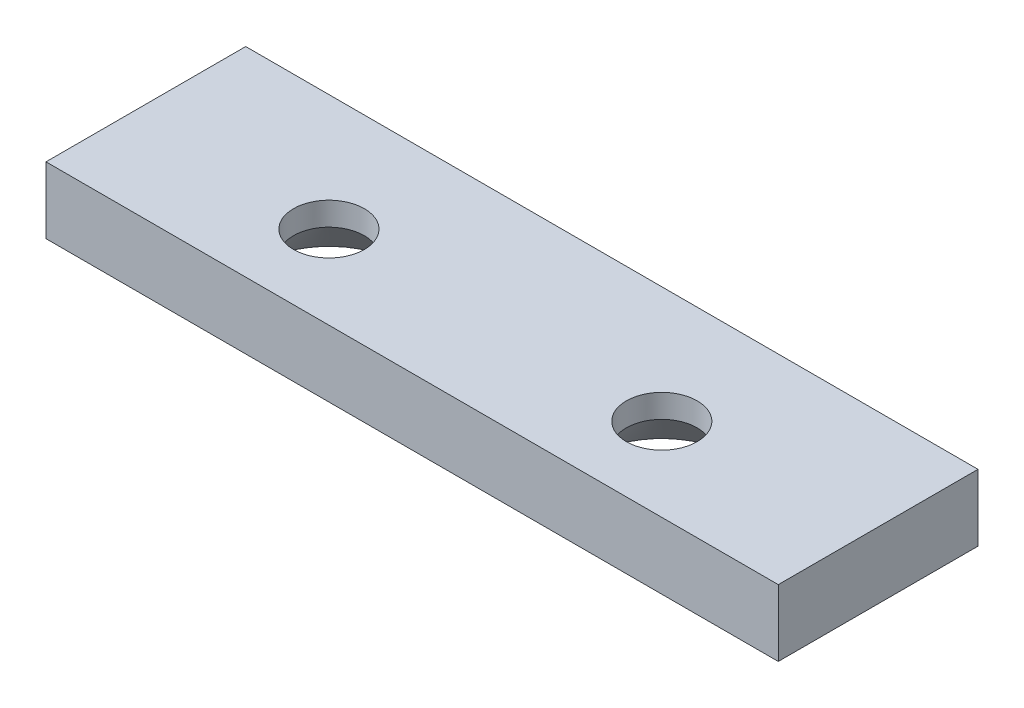
SolidWorks part; units mm, degrees
material "6061 Alloy"
ref_plane "Front Plane" through (0, 0, 0) normal (0, 0, 1) x (1, 0, 0)
ref_plane "Top Plane" through (0, 0, 0) normal (0, 1, 0) x (1, 0, 0)
ref_plane "Right Plane" through (0, 0, 0) normal (1, 0, 0) x (0, 0, -1)
sketch "Sketch1" plane through (0, 0, 0) normal (0, 1, 0) x (1, 0, 0)
  line L1 (34.925, -9.525) -> (-34.925, -9.525)
  line L2 (34.925, -9.525) -> (34.925, 9.525)
  line L3 (34.925, 9.525) -> (-34.925, 9.525)
  line L4 (-34.925, -9.525) -> (-34.925, 9.525)
  line L5 (34.925, -9.525) -> (-34.925, 9.525) construction
  line L6 (34.925, 9.525) -> (-34.925, -9.525) construction
  point P0 (0, 0)
  dimension "D1" = 69.85
  dimension "D2" = 19.05
extrude "Boss-Extrude1" add sketch "Sketch1" along normal blind 6.35
hole_wizard "CSK for 1/4 Flat Head Machine Screw1" positions "Sketch2" profile "Sketch3" countersink size "1/4" standard "ANSI Inch"
sketch "Sketch2" plane through (0, 0, 0) normal (0, -1, 0) x (-1, 0, 0)
  line L0 (34.925, -9.525) -> (-34.925, -9.525) construction
  line L1 (34.925, 9.525) -> (34.925, -9.525) construction
  line L2 (-34.925, -9.525) -> (-34.925, 9.525) construction
  point P0 (15.875, -1.5875)
  point P2 (-15.875, -1.5875)
  dimension "D1" = 7.9375
  dimension "D2" = 7.9375
  dimension "D3" = 19.05
  dimension "D4" = 19.05
sketch "Sketch3" plane through (-15.875, 0, 1.5875) normal (1, 0, 0) x (0, 0, -1)
  line L0 (0, 0) -> (0, 17.2698)
  line L1 (0, 17.2698) -> (3.3782, 15.24)
  line L2 (3.3782, 15.24) -> (3.3782, 4.1199)
  line L3 (3.3782, 4.1199) -> (6.9596, 0)
  line L5 (6.9596, 0) -> (0, 0)
  line L6 (-3.3782, 4.1199) -> (-6.9596, 0) construction
  line L10 (0, 17.2698) -> (-3.3782, 15.24) construction
  line L11 (0, -6.35) -> (0, 107.95) construction
  dimension "Hole Dia." = 6.7564
  dimension "Hole Depth" = 15.24
  dimension "Near C'Sink Dia." = 13.9192
  dimension "Near C'Sink Angle" = 82
  dimension "Drill Angle" = 118
